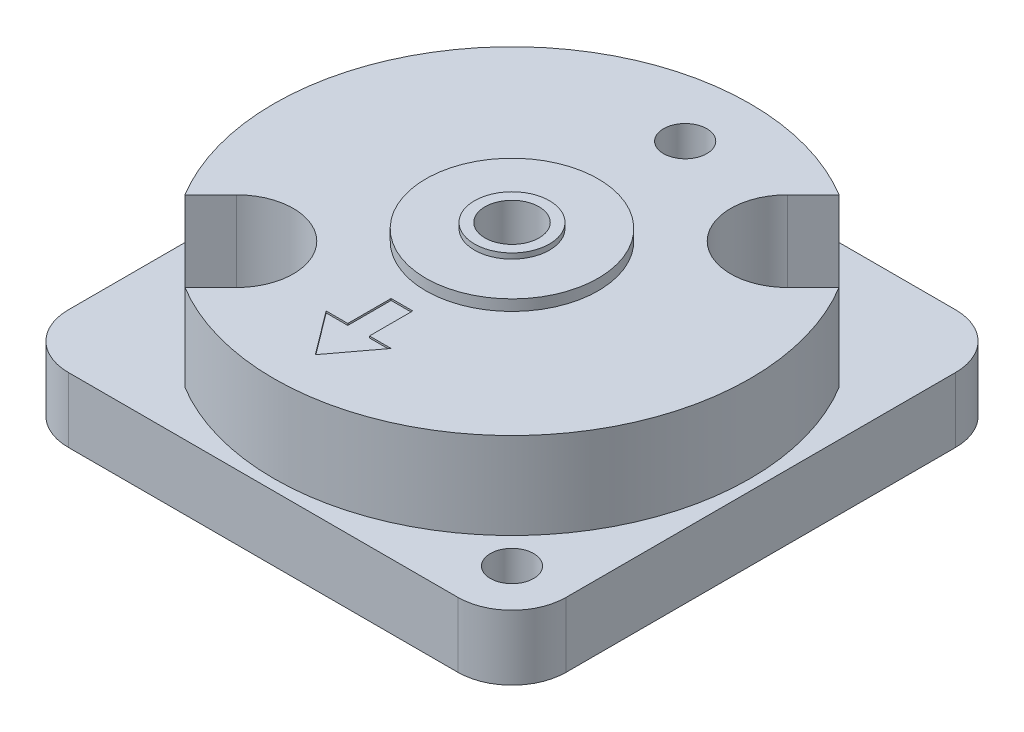
SolidWorks part; units mm, degrees
ref_plane "Front Plane" through (0, 0, 0) normal (0, 0, 1) x (1, 0, 0)
ref_plane "Top Plane" through (0, 0, 0) normal (0, 1, 0) x (1, 0, 0)
ref_plane "Right Plane" through (0, 0, 0) normal (1, 0, 0) x (0, 0, -1)
sketch "Sketch4" plane through (0, 0, 0) normal (0, 1, 0) x (1, 0, 0)
  line L1 (-36.5125, -36.5125) -> (36.5125, -36.5125)
  line L2 (-36.5125, -36.5125) -> (-36.5125, 36.5125)
  line L3 (-36.5125, 36.5125) -> (36.5125, 36.5125)
  line L4 (36.5125, -36.5125) -> (36.5125, 36.5125)
  line L5 (-36.5125, -36.5125) -> (36.5125, 36.5125) construction
  line L6 (-36.5125, 36.5125) -> (36.5125, -36.5125) construction
  point P0 (0, 0)
  dimension "D1" = 73.025
  dimension "D2" = 73.025
extrude "Boss-Extrude1" add sketch "Sketch4" along normal blind 9.525
sketch "Sketch7" plane through (0, 9.525, 0) normal (0, 1, 0) x (1, 0, 0)
  circle A0 centre (0, 0) radius 34.925
  dimension "D1" = 69.85
extrude "Boss-Extrude3" add sketch "Sketch7" along normal blind 12.7
fillet "Fillet1" radius 7.9502 4 edges at (36.5125, 4.7625, 36.5125) (-36.5125, 4.7625, 36.5125) (36.5125, 4.7625, -36.5125) (-36.5125, 4.7625, -36.5125)
sketch "Sketch8" plane through (0, 22.225, 0) normal (0, 1, 0) x (1, 0, 0)
  circle A0 centre (0, 0) radius 12.6365
  dimension "D1" = 25.273
extrude "Boss-Extrude4" add sketch "Sketch8" along normal blind 1.6002
sketch "Sketch9" plane through (0, 23.8252, 0) normal (0, 1, 0) x (1, 0, 0)
  circle A0 centre (0, 0) radius 5.4991
  dimension "D1" = 10.9982
extrude "Boss-Extrude5" add sketch "Sketch9" along normal blind 0.7874 contours A0
sketch "Sketch10" plane through (0, 22.225, 0) normal (0, 1, 0) x (1, 0, 0)
  line L0 (0, 28.575) -> (0, 0) construction
  line L1 (0, 0) -> (20.2056, 20.2056) construction
  line L2 (26.0966, 14.3145) -> (29.8738, 18.0917)
  line L3 (14.3145, 26.0966) -> (18.0917, 29.8738)
  line L4 (-5.891, 5.891) -> (14.3145, 26.0966) construction
  line L5 (5.891, -5.891) -> (26.0966, 14.3145) construction
  circle A0 centre (0, 0) radius 28.575 construction
  arc A1 (14.3145, 26.0966) -> (26.0966, 14.3145) centre (20.2056, 20.2056) ccw
  circle A2 centre (0, 0) radius 34.925 construction
  arc A3 (29.8738, 18.0917) -> (18.0917, 29.8738) centre (0, 0) ccw
  dimension "D1" = 57.15
  dimension "D2" = 45
  dimension "D3" = 8.3312
  dimension "D4" = 8.3312
extrude "Cut-Extrude1" cut sketch "Sketch10" against normal up to surface (12.7 mm away) up to face at (0, 9.525, 34.925)
pattern_circular "CirPattern1" count 2 over 360 about axis through (0, 0, 0) along (0, 1, 0) of "Cut-Extrude1"
sketch "Sketch11" plane through (0, 9.525, 0) normal (0, 1, 0) x (1, 0, 0)
  circle A0 centre (20.2056, 20.2056) radius 5.08
  circle A1 centre (-20.2056, -20.2056) radius 5.08
  dimension "D1" = 10.16
extrude "Cut-Extrude2" cut sketch "Sketch11" against normal through all
sketch "Sketch12" plane through (0, 9.525, 0) normal (0, 1, 0) x (1, 0, 0)
  line L0 (-36.5125, 28.5623) -> (-36.5125, -28.5623) construction
  line L1 (28.5623, 36.5125) -> (-28.5623, 36.5125) construction
  line L2 (-28.5623, -36.5125) -> (28.5623, -36.5125) construction
  line L3 (36.5125, -28.5623) -> (36.5125, 28.5623) construction
  point P0 (-28.5623, 28.5623)
  point P2 (28.5623, -28.5623)
  dimension "D1" = 7.9502
  dimension "D2" = 7.9502
  dimension "D3" = 7.9502
  dimension "D4" = 7.9502
hole_wizard "1/4 (0.25) Diameter Hole1" positions "Sketch12" profile "Sketch13" hole size "1/4" standard "ANSI Inch" end condition through all
sketch "Sketch13" plane through (-28.5623, 9.525, -28.5623) normal (1, 0, 0) x (0, 0, 1)
  line L0 (0, 0) -> (0, 9.525)
  line L1 (0, 9.525) -> (3.175, 9.525)
  line L2 (3.175, 9.525) -> (3.175, 0)
  line L5 (3.175, 0) -> (0, 0)
  line L11 (0, -6.35) -> (0, 107.95) construction
  dimension "Thru Hole Dia." = 6.35
  dimension "Thru Hole Depth" = 9.525
sketch "Sketch14" plane through (0, 22.225, 0) normal (0, 1, 0) x (1, 0, 0)
  circle A0 centre (0, 0) radius 25.4 construction
  point P0 (0, 25.4)
  dimension "D1" = 50.8
hole_wizard "1/4 (0.25) Diameter Hole2" positions "Sketch14" profile "Sketch15" hole size "1/4" standard "ANSI Inch"
sketch "Sketch15" plane through (0, 22.225, -25.4) normal (1, 0, 0) x (0, 0, 1)
  line L0 (0, 0) -> (0, 16.2079)
  line L1 (0, 16.2079) -> (3.175, 14.3002)
  line L2 (3.175, 14.3002) -> (3.175, 0)
  line L5 (3.175, 0) -> (0, 0)
  line L10 (0, 16.2079) -> (-3.175, 14.3002) construction
  line L11 (0, -6.35) -> (0, 107.95) construction
  dimension "Hole Dia." = 6.35
  dimension "Hole Depth" = 14.3002
  dimension "Drill Angle" = 118
sketch "Sketch16" plane through (0, 24.6126, 0) normal (0, 1, 0) x (1, 0, 0)
  point P0 (0, 0)
hole_wizard "3/8-16 Tapped Hole1" positions "Sketch16" profile "Sketch17" tap size "3/8-16" standard "ANSI Inch"
sketch "Sketch17" plane through (0, 24.6126, 0) normal (1, 0, 0) x (0, 0, 1)
  line L0 (0, 0) -> (0, 18.2597)
  line L1 (0, 18.2597) -> (3.9687, 15.875)
  line L2 (3.9687, 15.875) -> (3.9687, 0)
  line L5 (3.9687, 0) -> (0, 0)
  line L10 (0, 18.2597) -> (-3.9688, 15.875) construction
  line L11 (0, -6.35) -> (0, 107.95) construction
  dimension "Tap Drill Dia." = 7.9375
  dimension "Tap Drill Depth" = 15.875
  dimension "Drill Angle" = 118
cosmetic thread "Hole Thread1" parameters "D1"=15.875, "D2"=9.525
sketch "Sketch18" plane through (0, 22.225, 0) normal (0, 1, 0) x (1, 0, 0)
  line L0 (0, 0) -> (0, -34.925) construction
  line L1 (0, -28.8453) -> (4.7625, -22.4953)
  line L2 (4.7625, -22.4953) -> (1.5875, -22.4953)
  line L3 (1.5875, -22.4953) -> (1.5875, -16.1453)
  line L4 (1.5875, -16.1453) -> (-1.5875, -16.1453)
  line L5 (-1.5875, -22.4953) -> (-1.5875, -16.1453)
  line L6 (-4.7625, -22.4953) -> (-1.5875, -22.4953)
  line L7 (0, -28.8453) -> (-4.7625, -22.4953)
  arc A0 (-18.0917, -29.8738) -> (29.8738, 18.0917) centre (0, 0) ccw construction
  point P13 (0, -16.1453)
  dimension "D1" = 3.175
  dimension "D2" = 12.7
  dimension "D3" = 6.35
  dimension "D4" = 9.525
extrude "Cut-Extrude3" cut sketch "Sketch18" against normal blind 0.254
